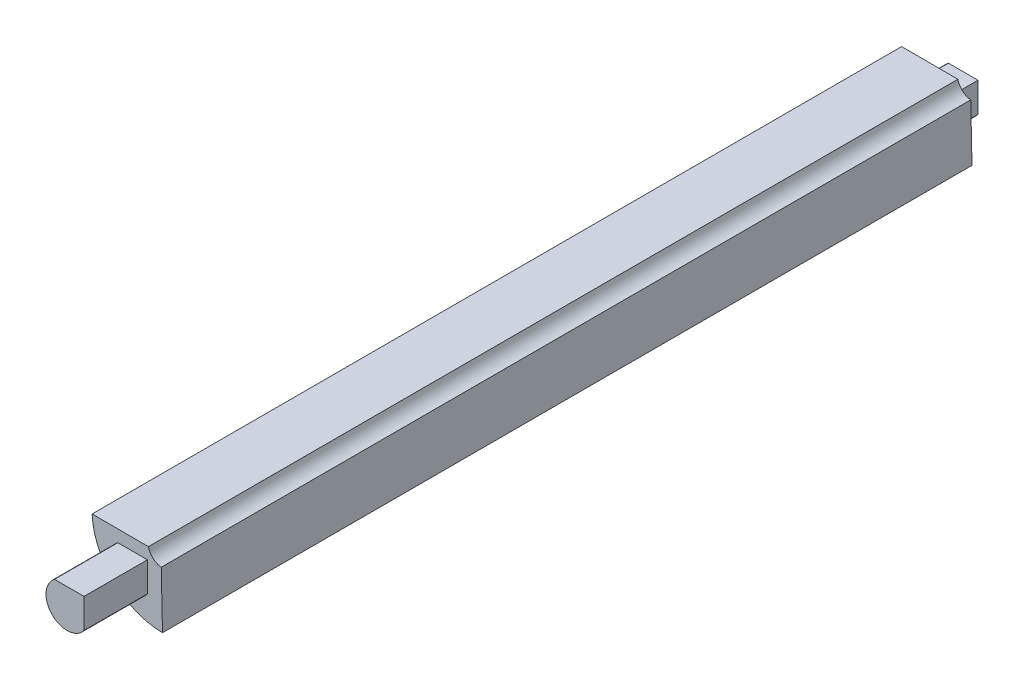
SolidWorks part; units mm, degrees
ref_plane "Front Plane" through (0, 0, 0) normal (0, 0, 1) x (1, 0, 0)
ref_plane "Top Plane" through (0, 0, 0) normal (0, 1, 0) x (1, 0, 0)
ref_plane "Right Plane" through (0, 0, 0) normal (1, 0, 0) x (0, 0, -1)
sketch "Sketch1" plane through (0, 0, 0) normal (0, 0, 1) x (1, 0, 0)
  line L0 (4.6738, -4.9699) -> (4.4943, 3.0006)
  line L1 (-5.3262, 4.6437) -> (2.6738, 4.6231)
  arc A0 (4.4943, 3.0006) -> (2.6738, 4.6231) centre (4.7136, 5.0793) cw
  arc A1 (4.6738, -4.9699) -> (-5.3262, 4.6437) centre (4.7136, 5.0793) cw
extrude "Boss-Extrude1" add sketch "Sketch1" along normal blind 115 contours L0 A0 L1 A1
sketch "Sketch2" plane through (0, 0, 115) normal (0, 0, 1) x (1, 0, 0)
  line L6 (-1.6736, 2.9299) -> (2.5264, 2.9299)
  line L7 (2.5264, 2.9299) -> (2.5264, -1.2701)
  arc A5 (2.5264, -1.2701) -> (-1.6736, 2.9299) centre (0.1203, 0.5238) cw
extrude "Boss-Extrude2" add sketch "Sketch2" along normal blind 9 and the other way blind 118
